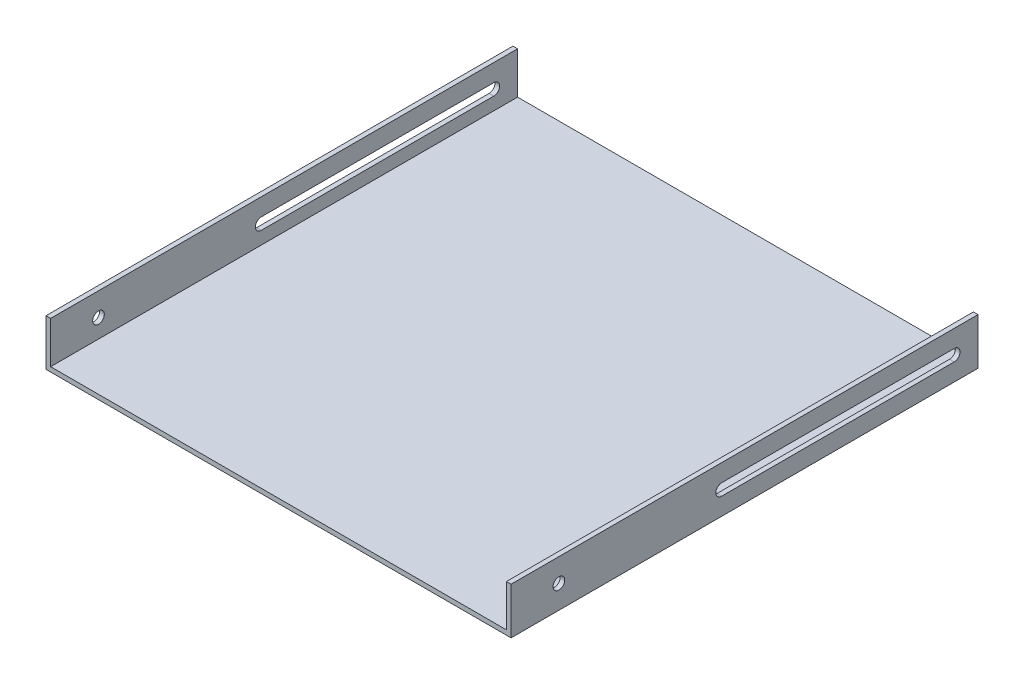
SolidWorks part; units mm, degrees
material "7050-T73510"
ref_plane "Front Plane" through (0, 0, 0) normal (0, 0, 1) x (1, 0, 0)
ref_plane "Top Plane" through (0, 0, 0) normal (0, 1, 0) x (1, 0, 0)
ref_plane "Right Plane" through (0, 0, 0) normal (1, 0, 0) x (0, 0, -1)
sketch "Sketch1" plane through (0, 0, 0) normal (0, 0, 1) x (1, 0, 0)
  line L0 (-98, 20) -> (-100, 20)
  line L1 (-100, 20) -> (-100, 0)
  line L2 (-100, 0) -> (100, 0)
  line L3 (100, 0) -> (100, 20)
  line L4 (100, 20) -> (98, 20)
  line L5 (98, 20) -> (98, 2)
  line L6 (98, 2) -> (-98, 2)
  line L7 (-98, 2) -> (-98, 20)
  point P8 (0, 0)
  dimension "D1" = 200
  dimension "D2" = 20
  dimension "D3" = 2
  dimension "D4" = 2
  dimension "D5" = 2
  dimension "D6" = 20
extrude "Boss-Extrude1" add sketch "Sketch1" along normal mid plane 320
sketch "Sketch2" plane through (100, 0, 0) normal (1, 0, 0) x (0, 0, -1)
  line L0 (-5.16, 10) -> (94.84, 10) construction
  line L1 (-5.16, 12.5) -> (94.84, 12.5)
  line L2 (-5.16, 7.5) -> (94.84, 7.5)
  line L3 (-160, 0) -> (160, 0) construction
  line L4 (-160, 0) -> (-160, 20) construction
  line L5 (44.84, 29.1154) -> (44.84, -12.8356) construction
  circle A0 centre (-75.16, 10) radius 2.5
  arc A1 (-5.16, 12.5) -> (-5.16, 7.5) centre (-5.16, 10) ccw
  arc A2 (94.84, 7.5) -> (94.84, 12.5) centre (94.84, 10) ccw
  point P4 (44.84, 10)
  dimension "D1" = 5
  dimension "D2" = 5
  dimension "D3" = 120
  dimension "D4" = 10
  dimension "D5" = 84.84
  dimension "D6" = 100
extrude "Cut-Extrude1" cut sketch "Sketch2" against normal through all
sketch "Sketch3" plane through (100, 0, 0) normal (1, 0, 0) x (0, 0, -1)
  line L1 (160, 0) -> (105.0618, 0)
  line L2 (160, 0) -> (160, 56.2465)
  line L3 (160, 56.2465) -> (105.0618, 56.2465)
  line L4 (105.0618, 0) -> (105.0618, 56.2465)
extrude "Cut-Extrude2" cut sketch "Sketch3" against normal through all
sketch "Sketch4" plane through (100, 0, 0) normal (1, 0, 0) x (0, 0, -1)
  line L1 (-160, 0) -> (-95.7339, 0)
  line L2 (-160, 0) -> (-160, 38.441)
  line L3 (-160, 38.441) -> (-95.7339, 38.441)
  line L4 (-95.7339, 0) -> (-95.7339, 38.441)
  dimension "D1" = 64.2661
extrude "Cut-Extrude3" cut sketch "Sketch4" against normal through all
